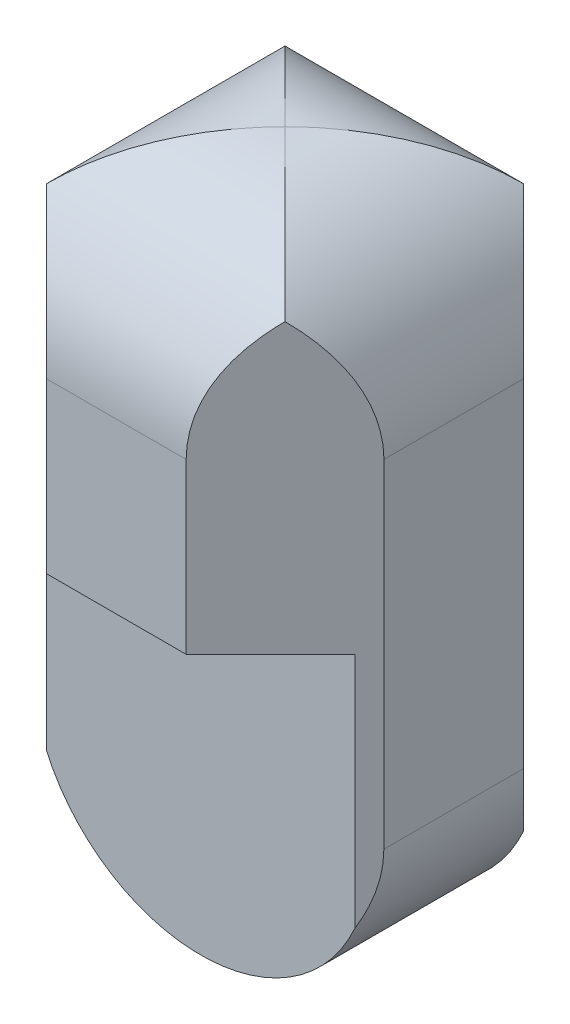
SolidWorks part; units mm, degrees
ref_plane "Front" through (0, 0, 0) normal (0, 0, 1) x (1, 0, 0)
ref_plane "Top" through (0, 0, 0) normal (0, 1, 0) x (1, 0, 0)
ref_plane "Right" through (0, 0, 0) normal (1, 0, 0) x (0, 0, -1)
sketch "草图1" plane through (0, 0, 0) normal (0, 1, 0) x (1, 0, 0)
  line L0 (-12.6518, 0) -> (13.462, 0) construction
  line L1 (0, 11.6722) -> (0, -14.1269) construction
  line L3 (10, 4.1421) -> (4.1421, 10)
  line L4 (4.1421, 10) -> (-4.1421, 10)
  line L5 (-4.1421, 10) -> (-10, 4.1421)
  line L6 (-10, 4.1421) -> (-10, -4.1421)
  line L7 (-10, -4.1421) -> (-4.1421, -10)
  line L8 (-4.1421, -10) -> (4.1421, -10)
  line L9 (4.1421, -10) -> (10, -4.1421)
  line L10 (10, -4.1421) -> (10, 4.1421)
  circle A0 centre (0, 0) radius 10 construction
extrude "凸台-拉伸1" add sketch "草图1" along normal blind 44
sketch "草图2" plane through (0, 0, 10) normal (0, 0, 1) x (1, 0, 0)
  line L0 (0, 0) -> (0, 24) construction
  line L7 (-10, 10) -> (-10, -2.3893)
  line L8 (-10, -2.3893) -> (10, -2.3893)
  line L9 (10, 10) -> (10, -2.3893)
  arc A1 (-10, 10) -> (10, 10) centre (0, 10) ccw
extrude "切除-拉伸1" cut sketch "草图2" against normal blind 66
sketch "草图4" plane through (0, 0, 10) normal (0, 0, 1) x (1, 0, 0)
  line L0 (10, 44) -> (10, 10) construction
  line L2 (-10, 10) -> (-10, 20)
  line L3 (-10, 20) -> (10, 20)
  line L4 (10, 10) -> (10, 20)
  arc A0 (-10, 10) -> (10, 10) centre (0, 10) ccw
extrude "切除-拉伸2" cut sketch "草图4" against normal blind 5
sketch "草图5" plane through (0, 0, -10) normal (0, 0, -1) x (-1, 0, 0)
  line L0 (10, 44) -> (10, 10) construction
  line L2 (-10, 10) -> (-10, 20)
  line L3 (-10, 20) -> (10, 20)
  line L4 (10, 10) -> (10, 20)
  arc A0 (-10, 10) -> (10, 10) centre (0, 10) ccw
extrude "切除-拉伸3" cut sketch "草图5" against normal blind 5
sketch "草图7" plane through (0, 0, 10) normal (0, 0, 1) x (1, 0, 0)
  line L0 (0, 44) -> (0, 0) construction
  line L1 (-4.1421, 44) -> (4.1421, 44) construction
  line L4 (-10, 30) -> (-10, 44.8839)
  line L5 (-10, 44.8839) -> (10, 44.8839)
  line L6 (10, 30) -> (10, 44.8839)
  arc A0 (10, 30) -> (-10, 30) centre (0, 30) ccw
extrude "切除-拉伸5" cut sketch "草图7" against normal blind 30
sketch "草图8" plane through (10, 0, 0) normal (1, 0, 0) x (0, 0, -1)
  line L0 (0, 40) -> (0, 0) construction
  line L1 (10, 40) -> (-10, 40) construction
  line L4 (-10, 30) -> (-10, 44.0756)
  line L5 (-10, 44.0756) -> (10, 44.0756)
  line L6 (10, 30) -> (10, 44.0756)
  arc A0 (10, 30) -> (-10, 30) centre (0, 30) ccw
  dimension "D1" = 10
extrude "切除-拉伸6" cut sketch "草图8" against normal blind 30
